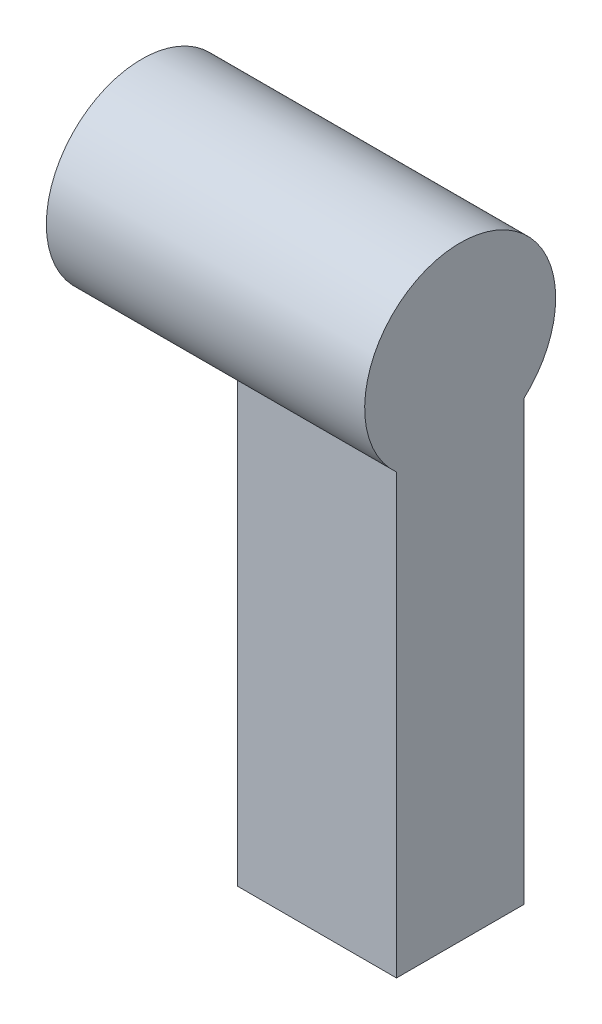
SolidWorks part; units mm, degrees
ref_plane "Front Plane" through (0, 0, 0) normal (0, 0, 1) x (1, 0, 0)
ref_plane "Top Plane" through (0, 0, 0) normal (0, 1, 0) x (1, 0, 0)
ref_plane "Right Plane" through (0, 0, 0) normal (1, 0, 0) x (0, 0, -1)
sketch "Sketch1" plane through (0, 0, 0) normal (1, 0, 0) x (0, 0, -1)
  circle A0 centre (0, 0) radius 15
  dimension "D1" = 30
extrude "Boss-Extrude1" add sketch "Sketch1" against normal blind 50
sketch "Sketch2" plane through (0, 0, 0) normal (0, 1, 0) x (1, 0, 0)
  line L5 (-50, -15) -> (0, -15) construction
  line L6 (0, 10) -> (-25, 10)
  line L10 (0, 10) -> (0, -10)
  line L11 (0, -10) -> (-25, -10)
  line L12 (-25, 10) -> (-25, -10)
  line L13 (0, 15) -> (-50, 15) construction
  line L14 (-50, 15) -> (-50, -15) construction
  point P0 (-17.5, 2.5)
  dimension "D1" = 5
  dimension "D2" = 5
  dimension "D3" = 25
  dimension "D4" = 25
extrude "Boss-Extrude2" add sketch "Sketch2" against normal blind 80
sketch "Sketch3" plane through (0, -80, 0) normal (0, -1, 0) x (1, 0, 0)
  circle A0 centre (-12.5, 0) radius 9
  dimension "D1" = 18
extrude "Cut-Extrude2" cut sketch "Sketch3" against normal blind 10
